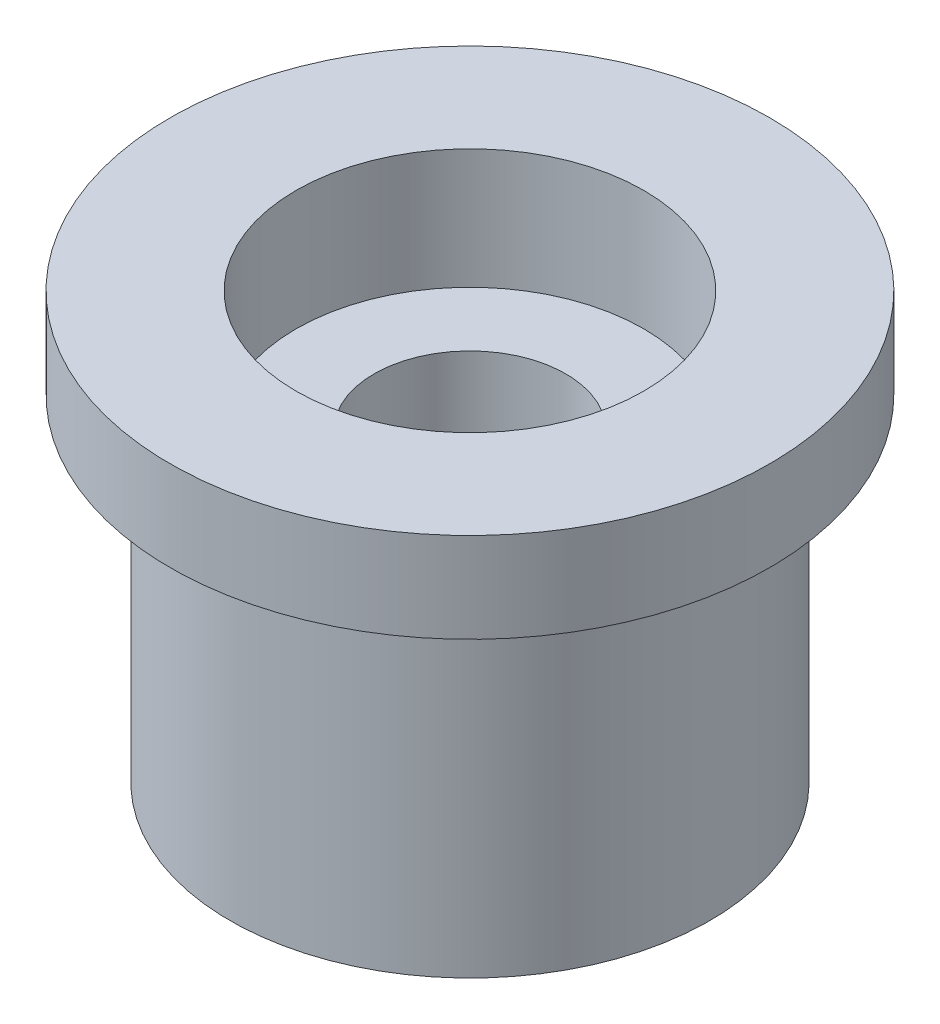
SolidWorks part; units mm, degrees
ref_plane "Front Plane" through (0, 0, 0) normal (0, 0, 1) x (1, 0, 0)
ref_plane "Top Plane" through (0, 0, 0) normal (0, 1, 0) x (1, 0, 0)
ref_plane "Right Plane" through (0, 0, 0) normal (1, 0, 0) x (0, 0, -1)
sketch "Sketch1" plane through (0, 0, 0) normal (0, 0, 1) x (1, 0, 0)
  line L0 (5, 7.1) -> (0, 7.1)
  line L1 (0, 7.1) -> (0, 5.6)
  line L2 (0, 5.6) -> (5, 5.6)
  line L3 (5, 5.6) -> (5, 7.1)
  line L4 (0, 7.1) -> (0, 5.6) construction
revolve "Revolve1" add sketch "Sketch1" angle 360 about L4
sketch "Sketch2" plane through (0, 5.6, 0) normal (0, -1, 0) x (1, 0, 0)
  circle A0 centre (0, 0) radius 4
extrude "Boss-Extrude1" add sketch "Sketch2" along normal blind 5.6
sketch "Sketch3" plane through (0, 0, 0) normal (0, -1, 0) x (1, 0, 0)
  line L0 (-1.1906, 2.8622) -> (-0.7861, 2.1615)
  line L1 (2.265, 0.4) -> (3.0741, 0.4)
  arc A0 (-0.7861, 2.1615) -> (2.265, 0.4) centre (0, 0) cw
  arc A1 (3.0741, 0.4) -> (-1.1906, 2.8622) centre (0, 0) ccw
extrude "Cut-Extrude1" cut sketch "Sketch3" against normal blind 4.3
sketch "Sketch4" plane through (0, 0, 0) normal (0, -1, 0) x (1, 0, 0)
  line L0 (-0.7861, -2.1615) -> (-1.1906, -2.8622)
  line L1 (3.0741, -0.4) -> (2.265, -0.4)
  arc A0 (-1.1906, -2.8622) -> (3.0741, -0.4) centre (0, 0) ccw
  arc A1 (2.265, -0.4) -> (-0.7861, -2.1615) centre (0, 0) cw
extrude "Cut-Extrude2" cut sketch "Sketch4" against normal blind 4.3
sketch "Sketch5" plane through (0, 0, 0) normal (0, -1, 0) x (1, 0, 0)
  line L0 (-1.8835, -2.4622) -> (-1.4789, -1.7615)
  line L1 (-1.4789, 1.7615) -> (-1.8835, 2.4622)
  arc A0 (-1.4789, -1.7615) -> (-1.4789, 1.7615) centre (0, 0) cw
  arc A1 (-1.8835, 2.4622) -> (-1.8835, -2.4622) centre (0, 0) ccw
extrude "Cut-Extrude3" cut sketch "Sketch5" against normal blind 4.3
hole_wizard "CBORE for M3 Hex Head Machine Screw1" positions "Sketch7" profile "Sketch6" counterbore size "M3" standard "ANSI Metric"
sketch "Sketch7" plane through (0, 7.1, 0) normal (0, 1, 0) x (1, 0, 0)
  point P0 (0, 0)
sketch "Sketch6" plane through (0, 7.1, 0) normal (1, 0, 0) x (0, 0, 1)
  line L0 (0, 0) -> (0, 7.1)
  line L1 (0, 7.1) -> (1.6, 7.1)
  line L3 (1.6, 7.1) -> (1.6, 2)
  line L4 (1.6, 2) -> (2.9, 2)
  line L5 (2.9, 2) -> (2.9, 0)
  line L7 (2.9, 0) -> (0, 0)
  line L11 (0, -6.35) -> (0, 107.95) construction
  dimension "Thru Hole Dia." = 3.2
  dimension "Thru Hole Depth" = 7.1
  dimension "C'Bore Dia." = 5.8
  dimension "C'Bore Depth" = 2
